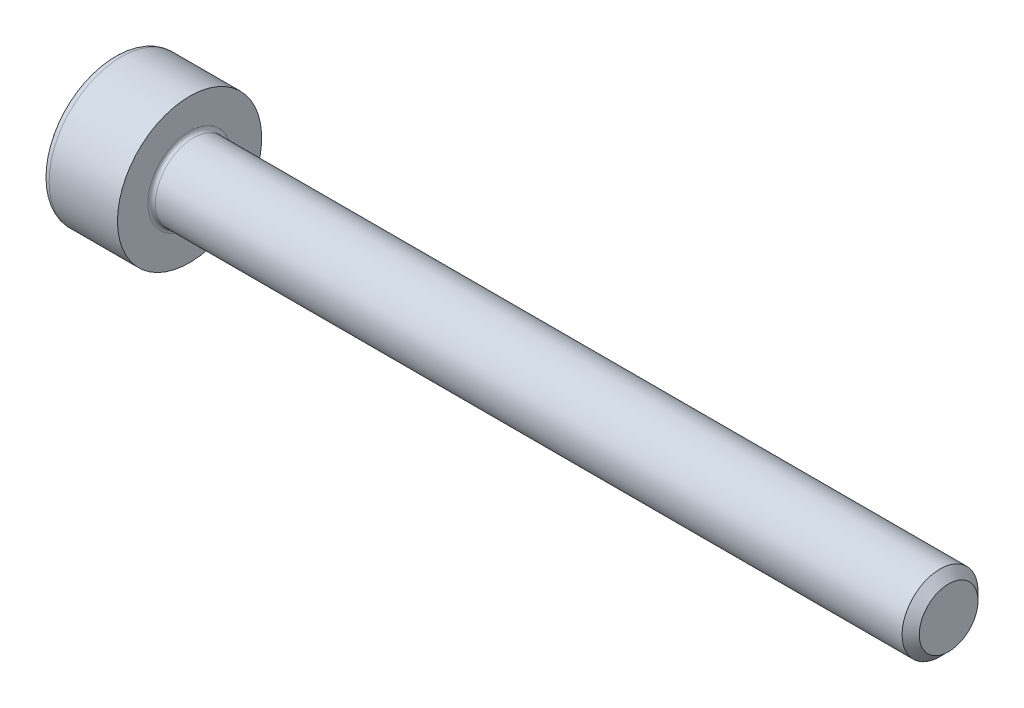
SolidWorks part; units mm, degrees
revolve "Base-Revolve" add sketch "BodySke"
sketch "BodySke" plane through (0, 0, 0) normal (0, 0, 1) x (1, 0, 0)
  line L0 (0, 0) -> (0, 1.9)
  line L1 (0, 1.9) -> (2, 1.9)
  line L2 (2, 1.9) -> (2, 1)
  line L3 (2, 1) -> (21.774, 1)
  line L4 (22, 0.774) -> (22, 0)
  line L5 (22, 0) -> (0, 0)
  line L6 (-31.75, 0) -> (127, 0) construction
  line L8 (22, 0.774) -> (21.774, 1)
  line L10 (22, -0.774) -> (21.774, -1) construction
  line L11 (2.4, 9.525) -> (2.4, 3.175) construction
  line L12 (-3, 9.525) -> (-3, 3.175) construction
  line L13 (-38, 9.525) -> (-38, 3.175) construction
  dimension "Head_ht" = 2
  dimension "Length" = 20
  dimension "Body_ch_ang" = 45
  dimension "Diameter" = 2
  dimension "Minor_dia" = 1.548
  dimension "Advance" = 0.4
  dimension "Thread_nom" = 25
  dimension "Thread_length" = 60
  dimension "Head_dia" = 3.8
cosmetic thread "ThreadCosmetic" [suppressed]
fillet "Fillet1" radius 0.1 1 edges at (2, 0, 1)
fillet "Fillet2" radius 0.2 1 edges at (0, 0, 1.9)
ref_plane "Plane1" through (0, 0, 0) normal (0, 0, 1) x (1, 0, 0)
ref_plane "Plane2" through (0, 0, 0) normal (0, 1, 0) x (1, 0, 0)
ref_plane "Plane3" through (0, 0, 0) normal (1, 0, 0) x (0, 0, -1)
sketch "Sketch2" plane through (0, 0, 0) normal (0, 0, 1) x (1, 0, 0)
  line L0 (0, 0.76) -> (1, 0.76)
  line L1 (1, 0.76) -> (1.4388, 0)
  line L2 (-31.75, 0) -> (127, 0) construction
  line L3 (1.4388, 0) -> (0, 0)
  line L4 (0, 0) -> (0, 0.76)
  line L6 (0, 0) -> (47.625, 0) construction
  dimension "D1" = 0.76
  dimension "D2" = 60
  dimension "Depth" = 1
revolve "Hex-PreBroach" cut sketch "Sketch2" angle 360 about L6
sketch "Sketch3" plane through (0, 0, 0) normal (-1, 0, 0) x (0, 0.5, 0.866)
  line L0 (0.4388, 0.76) -> (-0.4388, 0.76)
  line L1 (-0.4388, 0.76) -> (-0.8776, 0)
  line L2 (0.4388, 0.76) -> (0.8776, 0)
  line L3 (0.4388, -0.76) -> (0.8776, 0)
  line L4 (0.4388, -0.76) -> (-0.4388, -0.76)
  line L5 (-0.4388, -0.76) -> (-0.8776, 0)
  dimension "D1" = 0.76
  dimension "D2" = 0.76
  dimension "Hex_size" = 1.52
extrude "Hex" cut sketch "Sketch3" against normal blind 1
sketch "ThdSchSke" plane through (0, 0, 0) normal (0, 0, 1) x (1, 0, 0)
  line L0 (3.2, -0.774) -> (3.0418, -1)
  line L1 (3.2, -0.774) -> (3.3582, -1)
  line L2 (3.3582, -1) -> (3.3582, -1.25)
  line L3 (-3.175, 0) -> (5.1513, 0) construction
  line L4 (0, 1.7) -> (0, -1.7) construction
  line L5 (3.3582, -1.25) -> (3.0418, -1.25)
  line L6 (3.0418, -1.25) -> (3.0418, -1)
  dimension "Thread_minor" = 1.548
  dimension "Diameter" = 2
  dimension "Start" = 3.2
revolve "ThreadSchematic" [suppressed] cut sketch "ThdSchSke" angle 360 about L3
pattern_linear "ThdSchPat" [suppressed]
equation "\"D2@Sketch3\" = \"Hex_size@Sketch3\" / 2"
equation "\"D1@Sketch3\" = \"Hex_size@Sketch3\" / 2"
equation "\"D1@Sketch2\" = \"Hex_size@Sketch3\" / 2"
equation "\"Thread_minor@ThreadCosmetic\"  =  \"Minor_dia@BodySke\""
equation "\"Depth@Sketch2\" =  \"Key_eng@Hex\""
equation "\"Thread_length@ThreadCosmetic\" = ((sgn( (\"Length@BodySke\" - \"Advance@BodySke\" * 3.0) - \"Thread_nom@BodySke\" )-1)*( (\"Length@BodySke\" - \"Advance@BodySke\" * 3.0) - \"Thread_nom@BodySke\" ))/-2+ \"Thread_nom@BodySke\""
equation "\"Thread_minor@ThdSchSke\" = \"Minor_dia@BodySke\""
equation "\"Diameter@ThdSchSke\" = \"Diameter@BodySke\""
equation "\"Overcut@ThdSchSke\" = \"Diameter@BodySke\" * 1.25"
equation "\"Start@ThdSchSke\" = \"Head_ht@BodySke\" + \"Length@BodySke\" - \"Thread_length@ThreadCosmetic\"  '---Non-countersunk---"
equation "\"Num_threads@ThdSchPat\" = int( \"Thread_length@ThreadCosmetic\" / \"Advance@BodySke\" + 0.999 )  + 1"
equation "\"Advance@ThdSchPat\" = \"Thread_length@ThreadCosmetic\" /  (\"Num_threads@ThdSchPat\" - 1) 'relax it"
equation "\"Num_threads@ThdSchPat\" = \"Num_threads@ThdSchPat\" - sgn( \"Num_threads@ThdSchPat\" - 1) '---chamfered tips only---"
